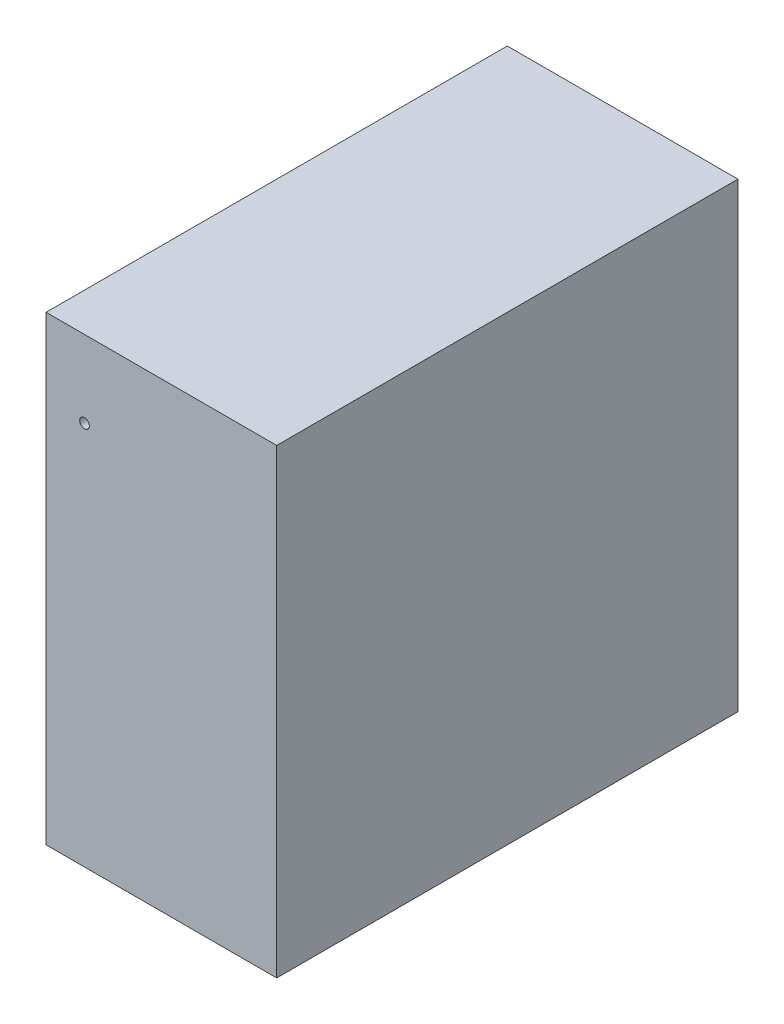
SolidWorks part; units mm, degrees
ref_plane "Front Plane" through (0, 0, 0) normal (0, 0, 1) x (1, 0, 0)
ref_plane "Top Plane" through (0, 0, 0) normal (0, 1, 0) x (1, 0, 0)
ref_plane "Right Plane" through (0, 0, 0) normal (1, 0, 0) x (0, 0, -1)
sketch "Sketch1" plane through (0, 0, 0) normal (0, 0, 1) x (1, 0, 0)
  line L1 (-76.2, 152.4) -> (76.2, 152.4)
  line L2 (-76.2, 152.4) -> (-76.2, -152.4)
  line L3 (-76.2, -152.4) -> (76.2, -152.4)
  line L4 (76.2, 152.4) -> (76.2, -152.4)
  line L5 (-76.2, 152.4) -> (76.2, -152.4) construction
  line L6 (-76.2, -152.4) -> (76.2, 152.4) construction
  circle A0 centre (-50.8, 101.6) radius 3.175
  point P0 (0, 0)
  point P8 (0, 0)
  point P9 (-50.7671, 101.5343)
  dimension "D3" = 6.35
  dimension "D1" = 152.4
  dimension "D2" = 304.8
  dimension "D4" = 50.8
extrude "Boss-Extrude1" add sketch "Sketch1" along normal blind 304.8
